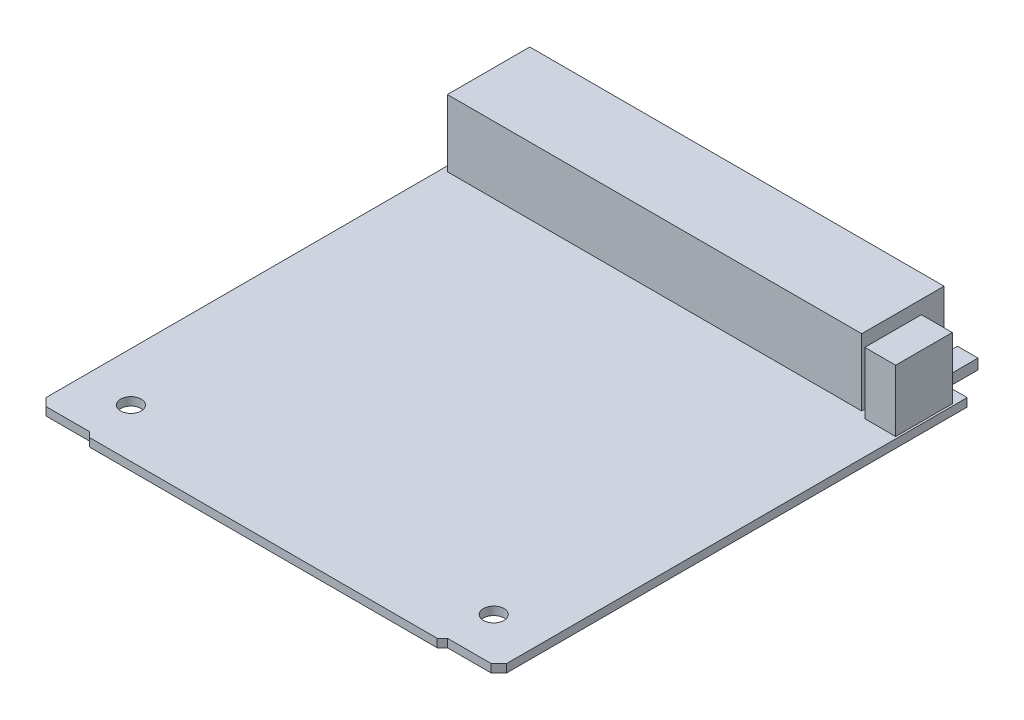
SolidWorks part; units mm, degrees
ref_plane "Front Plane" through (0, 0, 0) normal (0, 0, 1) x (1, 0, 0)
ref_plane "Top Plane" through (0, 0, 0) normal (0, 1, 0) x (1, 0, 0)
ref_plane "Right Plane" through (0, 0, 0) normal (1, 0, 0) x (0, 0, -1)
sketch "Sketch1" plane through (0, 0, 0) normal (0, 1, 0) x (1, 0, 0)
  line L0 (-44.75, 45.5) -> (44.75, -45.5) construction
  line L1 (-44.75, 45.5) -> (44.75, 45.5)
  line L2 (-44.75, 45.5) -> (-44.75, -45.5)
  line L3 (-44.75, -45.5) -> (-34.75, -45.5)
  line L4 (44.75, 45.5) -> (44.75, -45.5)
  line L5 (44.75, 45.5) -> (-44.75, -45.5) construction
  line L6 (-34.75, -45.5) -> (-33.75, -46.5)
  line L7 (-33.75, -46.5) -> (33.75, -46.5)
  line L8 (33.75, -46.5) -> (34.75, -45.5)
  line L9 (34.75, -45.5) -> (44.75, -45.5)
  point P4 (0, 0)
  point P5 (-32.3141, -46.5)
  point P11 (31.7372, -46.5)
  dimension "D1" = 89.5
  dimension "D2" = 92
  dimension "D3" = 1
  dimension "D4" = 10
  dimension "D5" = 45
  dimension "D6" = 45
extrude "Boss-Extrude1" add sketch "Sketch1" along normal blind 1.6
sketch "Sketch2" plane through (0, 1.6, 0) normal (0, 1, 0) x (1, 0, 0)
  line L0 (-44.75, 45.5) -> (-44.75, -45.5) construction
  line L1 (-43.75, 33) -> (36.75, 33)
  line L2 (-43.75, 33) -> (-43.75, 49)
  line L3 (-43.75, 49) -> (36.75, 49)
  line L4 (36.75, 33) -> (36.75, 49)
  line L5 (44.75, 45.5) -> (-44.75, 45.5) construction
  dimension "D1" = 16
  dimension "D2" = 80.5
  dimension "D3" = 1
  dimension "D4" = 3.5
extrude "Boss-Extrude2" add sketch "Sketch2" along normal blind 13
sketch "Sketch3" plane through (0, 1.6, 0) normal (0, 1, 0) x (1, 0, 0)
  line L2 (-35.25, -37) -> (-44.75, -37) construction
  line L3 (-44.75, 45.5) -> (-44.75, -45.5) construction
  line L4 (35.25, -37) -> (44.75, -37) construction
  line L5 (44.75, -45.5) -> (44.75, 45.5) construction
  line L6 (-33.75, -46.5) -> (33.75, -46.5) construction
  circle A0 centre (-35.25, -37) radius 2
  circle A1 centre (35.25, -37) radius 2
  point P4 (-35.25, -33.1831)
  dimension "D1" = 4
  dimension "D2" = 70.5
  dimension "D3" = 9.5
extrude "Cut-Extrude1" cut sketch "Sketch3" against normal up to next
chamfer "Chamfer1" distance 1.5 angle 45 2 edges at (44.75, 0.8, 45.5) (-44.75, 0.8, 45.5)
sketch "Sketch4" plane through (0, 1.6, 0) normal (0, 1, 0) x (1, 0, 0)
  line L1 (38.35, 43) -> (44.35, 43)
  line L2 (38.35, 43) -> (38.35, 32)
  line L3 (38.35, 32) -> (44.35, 32)
  line L4 (44.35, 43) -> (44.35, 32)
  line L6 (36.75, 49) -> (-43.75, 49) construction
  line L8 (36.75, 33) -> (36.75, 49) construction
  dimension "D1" = 11
  dimension "D2" = 6
  dimension "D3" = 7.6
  dimension "D4" = 6
extrude "Boss-Extrude3" add sketch "Sketch4" along normal blind 12
sketch "Sketch5" plane through (0, 0, -43) normal (0, 0, -1) x (-1, 0, 0)
  line L0 (-44.75, 0) -> (44.75, 0) construction
  line L1 (-43.35, 5.8) -> (-39.35, 5.8)
  line L2 (-43.35, 5.8) -> (-43.35, 3.8)
  line L3 (-43.35, 3.8) -> (-39.35, 3.8)
  line L4 (-39.35, 5.8) -> (-39.35, 3.8)
  line L5 (-36.75, 14.6) -> (-36.75, 1.6) construction
  point P6 (-39.35, 4.8)
  dimension "D1" = 4
  dimension "D2" = 2
  dimension "D3" = 3.8
  dimension "D4" = 2.6
extrude "Boss-Extrude4" add sketch "Sketch5" along normal blind 6
